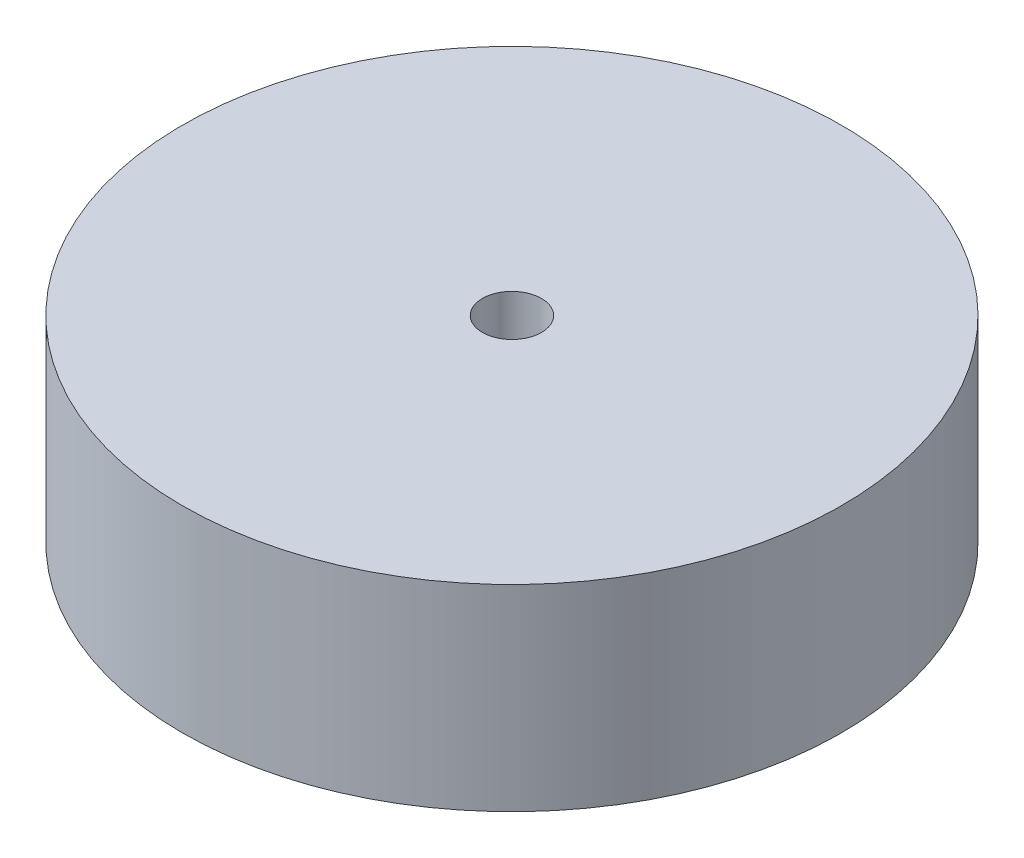
SolidWorks part; units mm, degrees
ref_plane "Front Plane" through (0, 0, 0) normal (0, 0, 1) x (1, 0, 0)
ref_plane "Top Plane" through (0, 0, 0) normal (0, 1, 0) x (1, 0, 0)
ref_plane "Right Plane" through (0, 0, 0) normal (1, 0, 0) x (0, 0, -1)
sketch "Sketch1" plane through (0, 0, 0) normal (0, 1, 0) x (1, 0, 0)
  circle A0 centre (0, 0) radius 3
  circle A1 centre (0, 0) radius 33.5
  dimension "D1" = 6
  dimension "D2" = 67
extrude "Boss-Extrude1" add sketch "Sketch1" along normal blind 20
